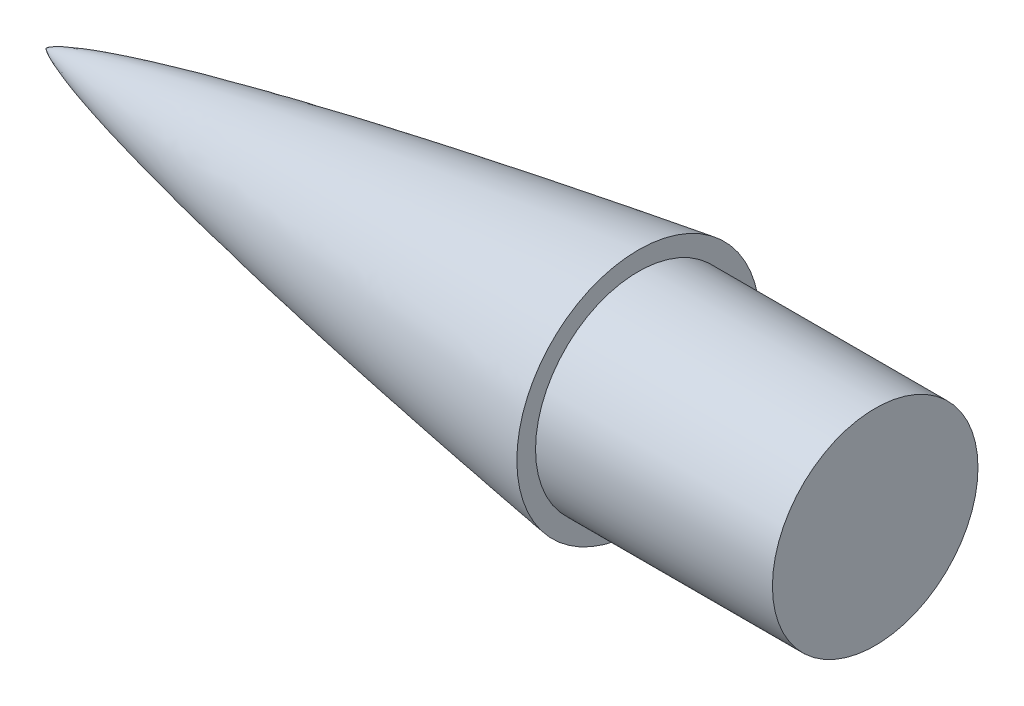
SolidWorks part; units mm, degrees
material "6061 Alloy"
ref_plane "Front Plane" through (0, 0, 0) normal (0, 0, 1) x (1, 0, 0)
ref_plane "Top Plane" through (0, 0, 0) normal (0, 1, 0) x (1, 0, 0)
ref_plane "Right Plane" through (0, 0, 0) normal (1, 0, 0) x (0, 0, -1)
sketch "Sketch1" plane through (0, 0, 0) normal (0, 0, 1) x (1, 0, 0)
  line L0 (0, 0) -> (63.5, 0)
  line L1 (63.5, 13.0281) -> (63.5, 0)
  spline S0 degree 4 poles (0, 0) (0.0023, 0.0063) (0.0084, 0.018) (0.0243, 0.0371) (0.0493, 0.0625) (0.0829, 0.0917) (0.1301, 0.1284) (0.1989, 0.1766) (0.3089, 0.2459) (0.4899, 0.3478) (0.8013, 0.5034) (1.3441, 0.7428) (2.303, 1.1127) (3.9199, 1.657) (6.5466, 2.4298) (10.0689, 3.3432) (14.3055, 4.3343) (18.9463, 5.3362) (23.6281, 6.2835) (28.274, 7.1781) (32.9994, 8.0463) (37.612, 8.8653) (42.4237, 9.6866) (46.9196, 10.4362) (51.9458, 11.2441) (56.1036, 11.9022) (61.2491, 12.6899) (64.105, 13.1202) (66.9381, 13.541) (68.8393, 13.8216) (69.3158, 13.8902) (69.8978, 13.976) knots 0 0 0 0 0 0.000373 0.000746 0.001375 0.002003 0.002859 0.004098 0.006082 0.00928 0.014497 0.023583 0.039337 0.0668 0.110142 0.176804 0.243466 0.310128 0.376789 0.443451 0.510113 0.576774 0.643436 0.710098 0.776759 0.843421 0.910083 0.955041 0.977521 1 1 1 1 1 construction
  spline S1 degree 4 poles (0, 0) (0.0023, 0.0063) (0.0084, 0.018) (0.0243, 0.0371) (0.0493, 0.0625) (0.0829, 0.0917) (0.1301, 0.1284) (0.1989, 0.1766) (0.3089, 0.2459) (0.4899, 0.3478) (0.8013, 0.5034) (1.3441, 0.7428) (2.303, 1.1127) (3.9199, 1.657) (6.5466, 2.4298) (10.0689, 3.3432) (14.3055, 4.3343) (18.9463, 5.3362) (23.6281, 6.2835) (28.274, 7.1781) (32.9994, 8.0463) (37.612, 8.8653) (42.4237, 9.6866) (46.9196, 10.4362) (51.9458, 11.2441) (56.1036, 11.9022) (60.3047, 12.5453) (62.4292, 12.8672) (63.5, 13.0281) knots 0 0 0 0 0 0.000373 0.000746 0.001375 0.002003 0.002859 0.004098 0.006082 0.00928 0.014497 0.023583 0.039337 0.0668 0.110142 0.176804 0.243466 0.310128 0.376789 0.443451 0.510113 0.576774 0.643436 0.710098 0.776759 0.843421 0.910083 0.910083 0.910083 0.910083 0.910083
  dimension "D1" = 63.5
revolve "Revolve1" add sketch "Sketch1" angle 360 about L0
sketch "Sketch2" plane through (63.5, 0, 0) normal (1, 0, 0) x (0, 0, -1)
  circle A0 centre (0, 0) radius 11.0215
  circle A1 centre (0, 0) radius 13.0281
  circle A2 centre (0, 0) radius 13.0281 construction
  dimension "D1" = 0
  dimension "D2" = 2.0066
extrude "Boss-Extrude1" add sketch "Sketch2" along normal blind 25.4
